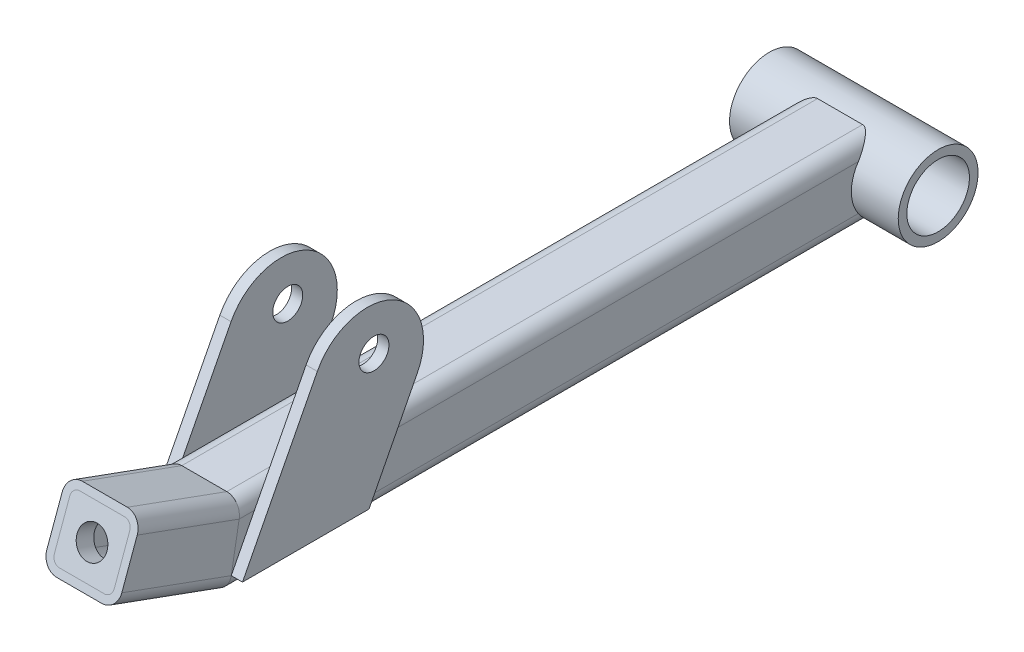
SolidWorks part; units mm, degrees
ref_plane "Front Plane" through (0, 0, 0) normal (0, 0, 1) x (1, 0, 0)
ref_plane "Top Plane" through (0, 0, 0) normal (0, 1, 0) x (1, 0, 0)
ref_plane "Right Plane" through (0, 0, 0) normal (1, 0, 0) x (0, 0, -1)
sketch "Sketch1" plane through (0, 0, 0) normal (0, 1, 0) x (1, 0, 0)
  line L0 (-22.5, 0) -> (22.5, 0)
  line L1 (0, 0) -> (0, -175)
  point P4 (0, 0)
  dimension "D1" = 45
  dimension "D2" = 175
sketch3d "3DSketch1"
  line L0 (0, 0, 175) -> (0, 10.2606, 203.1908)
  line L1 (0, 0, 0) -> (0, 0, 175) construction
  dimension "D1" = 30
  dimension "D2" = 160
other "Square tube 20 X 20 X 2(1)"
ref_plane "Plane1" through (0, 0, 0) normal (0, 0, 1) x (1, 0, 0)
sketch "Sketch14" plane through (0, 0, 0) normal (0, 0, 1) x (1, 0, 0)
  line L0 (-6, -8) -> (6, -8)
  line L1 (-8, -6) -> (-8, 6)
  line L2 (6, 8) -> (-6, 8)
  line L3 (8, 6) -> (8, -6)
  line L4 (-6, -10) -> (6, -10)
  line L5 (-10, -6) -> (-10, 6)
  line L6 (6, 10) -> (-6, 10)
  line L7 (10, 6) -> (10, -6)
  arc A0 (10, 6) -> (6, 10) centre (6, 6) ccw
  arc A1 (6, -10) -> (10, -6) centre (6, -6) ccw
  arc A2 (-10, -6) -> (-6, -10) centre (-6, -6) ccw
  arc A3 (-6, 10) -> (-10, 6) centre (-6, 6) ccw
  arc A4 (-6, 8) -> (-8, 6) centre (-6, 6) ccw
  arc A5 (8, 6) -> (6, 8) centre (6, 6) ccw
  arc A6 (6, -8) -> (8, -6) centre (6, -6) ccw
  arc A7 (-8, -6) -> (-6, -8) centre (-6, -6) ccw
  point P0 (-10, 0)
  point P1 (10, 0)
  point P2 (0, 10)
  point P3 (0, -10)
  point P4 (0, 0)
  point P5 (-10, -10)
  point P6 (10, -10)
  point P7 (10, 10)
  point P8 (-10, 10)
  point P33 (0, 0)
  dimension "D1" = 4
  dimension "Thickness" = 2
  dimension "V_leg" = 20
other "Pipe 21.3 X 2.3(1)"
ref_plane "Plane3" through (-22.5, 0, 0) normal (1, 0, 0) x (0, 0, -1)
sketch "Sketch15" plane through (-22.5, 0, 0) normal (1, 0, 0) x (0, 0, -1)
  circle A0 centre (0, 0) radius 8.35
  circle A1 centre (0, 0) radius 10.65
  point P3 (0, 0)
  dimension "In_dia" = 16.7
  dimension "Out_dia" = 21.3
other "Trim/Extend1"
sketch "Sketch16" plane through (-10, 0, 0) normal (-1, 0, 0) x (0, 0, 1)
  line L1 (176.058, -6) -> (156.1001, 32.6922)
  line L2 (142.3021, -6) -> (129.438, 18.9396)
  line L3 (176.058, -6) -> (142.3021, -6)
  arc A0 (156.1001, 32.6922) -> (129.438, 18.9396) centre (142.769, 25.8159) ccw
  circle A2 centre (140.9873, 29.27) radius 4
  dimension "D1" = 8
  dimension "D2" = 30
extrude "Boss-Extrude1" add sketch "Sketch16" along normal blind 3 separate body
sketch "Sketch17" plane through (10, 0, 0) normal (1, 0, 0) x (0, 0, -1)
  line L3 (-156.1001, 32.6922) -> (-176.058, -6)
  line L4 (-142.3021, -6) -> (-129.438, 18.9396)
  line L5 (-176.058, -6) -> (-142.3021, -6)
  line L6 (-156.1001, 32.6922) -> (-176.058, -6)
  line L7 (-142.3021, -6) -> (-129.438, 18.9396)
  line L8 (-176.058, -6) -> (-142.3021, -6)
  circle A0 centre (-140.9873, 29.27) radius 4 construction
  circle A1 centre (-140.9873, 29.27) radius 4
  arc A3 (-129.438, 18.9396) -> (-156.1001, 32.6922) centre (-142.769, 25.8159) ccw
  arc A4 (-129.438, 18.9396) -> (-156.1001, 32.6922) centre (-142.769, 25.8159) ccw
  dimension "D2" = 0
extrude "Boss-Extrude2" add sketch "Sketch17" along normal blind 3 separate body
sketch "Sketch18" plane through (0, 66.5045, 182.7197) normal (0, 0.342, 0.9397) x (1, 0, 0)
  line L0 (8, -65.8535) -> (8, -53.8535) construction
  line L1 (-6, -67.8535) -> (6, -67.8535) construction
  line L2 (-8, -53.8535) -> (-8, -65.8535) construction
  line L3 (6, -51.8535) -> (-6, -51.8535) construction
  line L4 (8, -65.8535) -> (8, -53.8535)
  line L5 (-6, -67.8535) -> (6, -67.8535)
  line L6 (-8, -53.8535) -> (-8, -65.8535)
  line L7 (6, -51.8535) -> (-6, -51.8535)
  arc A0 (6, -67.8535) -> (8, -65.8535) centre (6, -65.8535) ccw construction
  arc A1 (-8, -65.8535) -> (-6, -67.8535) centre (-6, -65.8535) ccw construction
  arc A2 (-6, -51.8535) -> (-8, -53.8535) centre (-6, -53.8535) ccw construction
  arc A3 (8, -53.8535) -> (6, -51.8535) centre (6, -53.8535) ccw construction
  arc A4 (6, -67.8535) -> (8, -65.8535) centre (6, -65.8535) ccw
  arc A5 (-8, -65.8535) -> (-6, -67.8535) centre (-6, -65.8535) ccw
  arc A6 (-6, -51.8535) -> (-8, -53.8535) centre (-6, -53.8535) ccw
  arc A7 (8, -53.8535) -> (6, -51.8535) centre (6, -53.8535) ccw
  circle A8 centre (0, -59.8535) radius 4
  dimension "D1" = 8
extrude "Boss-Extrude3" add sketch "Sketch18" against normal blind 5 separate body
